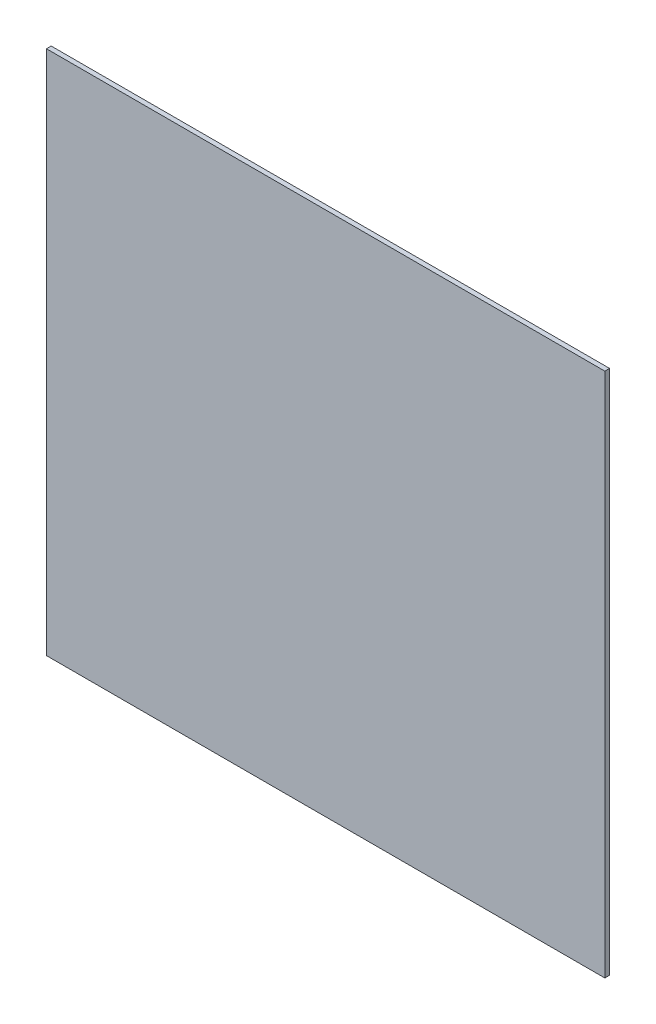
SolidWorks part; units mm, degrees
ref_plane "Front Plane" through (0, 0, 0) normal (0, 0, 1) x (1, 0, 0)
ref_plane "Top Plane" through (0, 0, 0) normal (0, 1, 0) x (1, 0, 0)
ref_plane "Right Plane" through (0, 0, 0) normal (1, 0, 0) x (0, 0, -1)
sketch "Sketch1" plane through (0, 0, 0) normal (0, 0, 1) x (1, 0, 0)
  line L1 (0, 0) -> (150, 0)
  line L2 (0, 0) -> (0, 141.19)
  line L3 (0, 141.19) -> (150, 141.19)
  line L4 (150, 0) -> (150, 141.19)
  dimension "D1" = 141.19
  dimension "D2" = 150
extrude "Boss-Extrude1" add sketch "Sketch1" along normal blind 1.27
